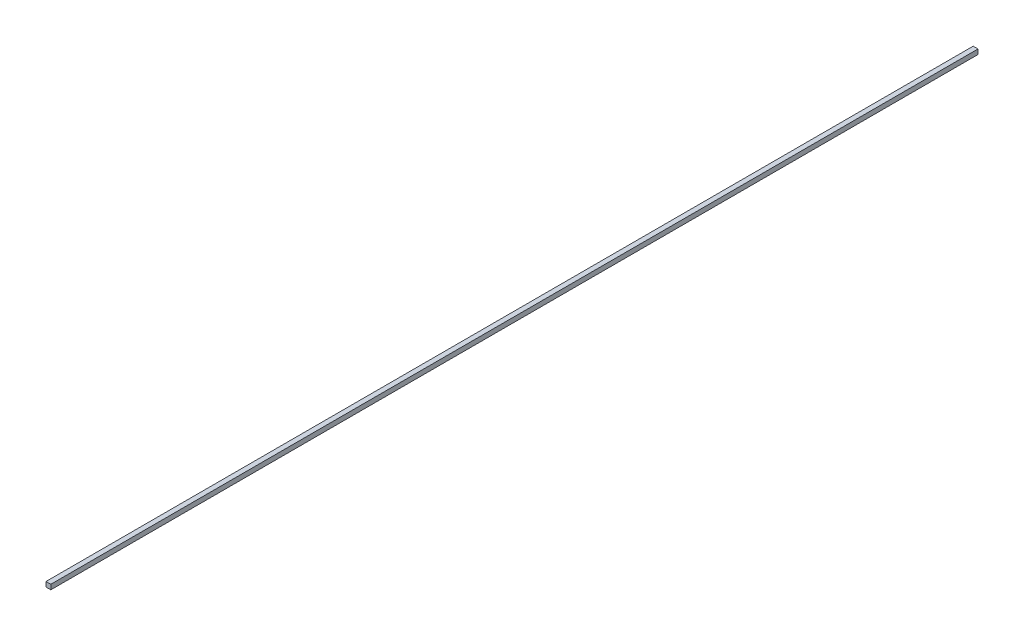
SolidWorks part; units mm, degrees
ref_plane "Front Plane" through (0, 0, 0) normal (0, 0, 1) x (1, 0, 0)
ref_plane "Top Plane" through (0, 0, 0) normal (0, 1, 0) x (1, 0, 0)
ref_plane "Right Plane" through (0, 0, 0) normal (1, 0, 0) x (0, 0, -1)
sketch "Sketch1" plane through (0, 0, 0) normal (0, 0, 1) x (1, 0, 0)
  line L0 (-3.175, 3.175) -> (-3.175, -3.175) construction
  line L1 (-3.175, 3.175) -> (3.175, 3.175) construction
  line L2 (-3.175, 0) -> (0, 0) construction
  line L3 (0, 0) -> (0, 3.175) construction
  dimension "Thickness" = 6.35
  dimension "Width" = 6.35
ref_plane "Plane1" through (-3.175, 3.175, 0) normal (0, -1, 0) x (-1, 0, 0)
sketch "Sketch2" plane through (-3.175, 3.175, 0) normal (0, 1, 0) x (1, 0, 0)
  line L0 (3.175, -609.6) -> (3.175, 609.6) construction
  point P2 (3.175, -596.9)
  point P3 (3.175, 596.9)
  dimension "Length" = 1219.2
  dimension "D1" = 12.7
  dimension "D2" = 12.7
sketch "Sketch3" plane through (0, 0, 0) normal (0, 0, 1) x (1, 0, 0)
  line L1 (-3.175, -3.175) -> (3.175, -3.175)
  line L2 (-3.175, -3.175) -> (-3.175, 3.175)
  line L3 (-3.175, 3.175) -> (3.175, 3.175)
  line L4 (3.175, -3.175) -> (3.175, 3.175)
  line L5 (0, 3.175) -> (0, -3.175) construction
  line L6 (-3.175, 0) -> (3.175, 0) construction
  line L7 (-3.175, 0) -> (0, 0) construction
extrude "Boss-Extrude1" add sketch "Sketch3" along normal up to vertex (609.6 mm away) and the other way up to vertex (609.6 mm away) up to point (0, 3.175, 609.6) other way up to point (0, 3.175, -609.6)
equation "\"D1@Sketch2\"=\"Width@Sketch1\"*2"
equation "\"D2@Sketch2\"=\"D1@Sketch2\""
